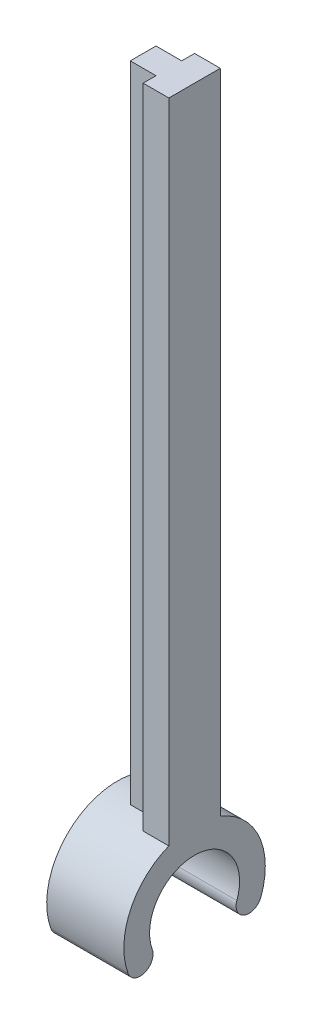
SolidWorks part; units mm, degrees
ref_plane "Front" through (0, 0, 0) normal (0, 0, 1) x (1, 0, 0)
ref_plane "Top" through (0, 0, 0) normal (0, 1, 0) x (1, 0, 0)
ref_plane "Right" through (0, 0, 0) normal (1, 0, 0) x (0, 0, -1)
sketch "Sketch1" plane through (0, 0, 0) normal (1, 0, 0) x (0, 0, -1)
  line L0 (0, 0) -> (-5.5, 0)
  line L1 (0, 0) -> (-5.1683, -1.8811)
  line L2 (0, 50) -> (0, -50) construction
  line L3 (0, 0) -> (5.1683, -1.8811)
  line L4 (-5.1683, -1.8811) -> (-4.2286, -1.5391)
  circle A0 centre (0, 0) radius 3.5
  circle A1 centre (0, 0) radius 5.5
  arc A2 (-5.1683, -1.8811) -> (-3.2889, -1.1971) centre (-4.2286, -1.5391) ccw
  arc A3 (5.1683, -1.8811) -> (3.2889, -1.1971) centre (4.2286, -1.5391) cw
  dimension "D1" = 20
  dimension "D3" = 11
  dimension "D4" = 7
  dimension "D2" = 1
extrude "Boss-Extrude1" add sketch "Sketch1" against normal blind 4 and the other way blind 2 contours L3 A1 L0 A0 | A3 L3 | L0 A1 L1 A0 | L1 A2
sketch "Sketch2" plane through (0, 0, 0) normal (1, 0, 0) x (0, 0, -1)
  line L0 (0, 0) -> (0, 5.5)
  line L1 (0, 5.5) -> (0, 3.5)
  line L2 (0, 3.5) -> (-2, 3.5)
  line L4 (-2, 3.5) -> (2, 3.5)
  line L5 (-2, 3.5) -> (-2, 55.5)
  line L6 (-2, 55.5) -> (2, 55.5)
  line L7 (2, 3.5) -> (2, 55.5)
  arc A0 (5.1683, -1.8811) -> (-5.1683, -1.8811) centre (0, 0) ccw construction
  dimension "D1" = 2
  dimension "D2" = 2
  dimension "D3" = 4
  dimension "D4" = 52
extrude "Boss-Extrude2" add sketch "Sketch2" along normal blind 2
sketch "Sketch3" plane through (0, 0, 0) normal (1, 0, 0) x (0, 0, -1)
  line L0 (0, 55.5) -> (-1, 55.5)
  line L1 (-2, 55.5) -> (2, 55.5) construction
  line L3 (-1, 55.5) -> (1, 55.5)
  line L4 (-1, 55.5) -> (-1, 3.5)
  line L5 (-1, 3.5) -> (1, 3.5)
  line L6 (1, 55.5) -> (1, 3.5)
  dimension "D1" = 1
  dimension "D2" = 52
  dimension "D3" = 2
extrude "Boss-Extrude3" add sketch "Sketch3" against normal blind 2 contours L6 L3 L0 L4 L5
